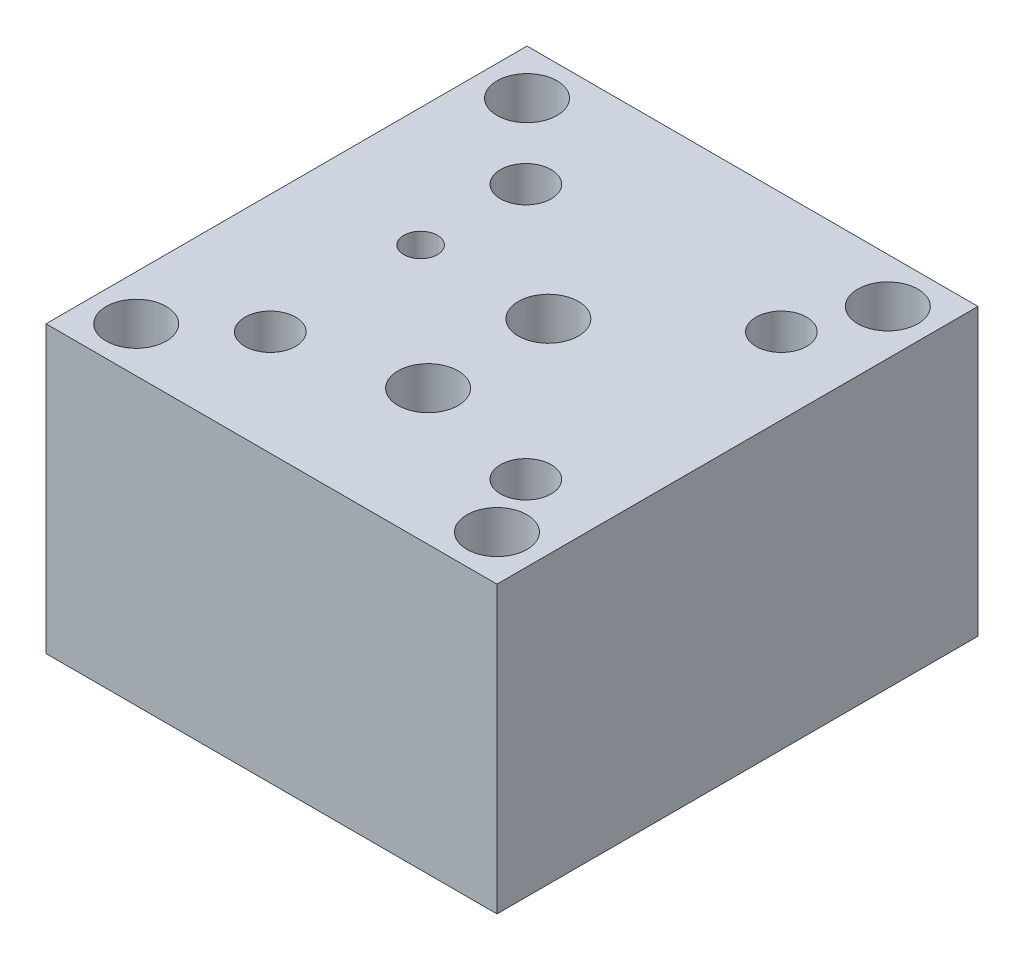
SolidWorks part; units mm, degrees
ref_plane "Front Plane" through (0, 0, 0) normal (0, 0, 1) x (1, 0, 0)
ref_plane "Top Plane" through (0, 0, 0) normal (0, 1, 0) x (1, 0, 0)
ref_plane "Right Plane" through (0, 0, 0) normal (1, 0, 0) x (0, 0, -1)
sketch "Sketch1" plane through (0, 0, 0) normal (0, 1, 0) x (1, 0, 0)
  line L1 (-47.625, -50.8) -> (47.625, -50.8)
  line L2 (-47.625, -50.8) -> (-47.625, 50.8)
  line L3 (-47.625, 50.8) -> (47.625, 50.8)
  line L4 (47.625, -50.8) -> (47.625, 50.8)
  line L5 (-47.625, -50.8) -> (47.625, 50.8) construction
  line L6 (-47.625, 50.8) -> (47.625, -50.8) construction
  point P0 (0, 0)
  dimension "D1" = 47.625
  dimension "D2" = 50.8
extrude "Boss-Extrude1" add sketch "Sketch1" along normal mid plane 60.325
sketch "Sketch2" plane through (0, 0, 0) normal (0, 1, 0) x (1, 0, 0)
  circle A0 centre (-38.1, -41.275) radius 4.3688
  circle A1 centre (38.1, -41.275) radius 4.3688
  circle A2 centre (-38.1, 41.275) radius 4.3688
  circle A3 centre (38.1, 41.275) radius 4.3688
  point P8 (0, 0)
  dimension "D1" = 8.7376
  dimension "D2" = 8.7376
  dimension "D3" = 8.7376
  dimension "D4" = 8.7376
  dimension "D5" = 76.2
  dimension "D6" = 82.55
  dimension "D7" = 38.1
  dimension "D8" = 41.275
extrude "Cut-Extrude2" cut sketch "Sketch2" against normal blind 101.6 from offset 30.1625
sketch "Sketch3" plane through (0, 0, 0) normal (0, 1, 0) x (1, 0, 0)
  circle A0 centre (-38.1, -41.275) radius 6.35
  circle A1 centre (38.1, -41.275) radius 6.35
  circle A2 centre (-38.1, 41.275) radius 6.35
  circle A3 centre (38.1, 41.275) radius 6.35
  point P8 (0, 0)
  dimension "D1" = 12.7
  dimension "D2" = 12.7
  dimension "D3" = 12.7
  dimension "D4" = 12.7
  dimension "D5" = 76.2
  dimension "D6" = 82.55
  dimension "D7" = 38.1
  dimension "D8" = 41.275
extrude "Cut-Extrude4" cut sketch "Sketch3" against normal blind 25.4 from offset 30.1625
sketch "Sketch4" plane through (0, 0, 0) normal (0, 1, 0) x (1, 0, 0)
  circle A0 centre (-22.479, -28.575) radius 5.3578
  circle A1 centre (31.496, -28.575) radius 5.3578
  circle A2 centre (-22.479, 25.4) radius 5.3578
  circle A3 centre (31.496, 25.4) radius 5.3578
  point P8 (0, 0)
  dimension "D1" = 10.7156
  dimension "D2" = 10.7156
  dimension "D3" = 10.7156
  dimension "D4" = 10.7156
  dimension "D5" = 53.975
  dimension "D6" = 53.975
  dimension "D7" = 22.479
  dimension "D8" = 28.575
extrude "Cut-Extrude6" cut sketch "Sketch4" against normal blind 20.32 from offset 30.1625
sketch "Sketch5" plane through (0, 0, 0) normal (0, 1, 0) x (1, 0, 0)
  circle A0 centre (4.5085, -22.225) radius 6.35
  circle A1 centre (4.5085, 3.175) radius 6.35
  point P4 (0, 0)
  dimension "D1" = 12.7
  dimension "D2" = 12.7
  dimension "D3" = 25.4
  dimension "D4" = 4.5085
  dimension "D5" = 22.225
extrude "Cut-Extrude8" cut sketch "Sketch5" against normal blind 45.72 from offset 30.1625
sketch "Sketch6" plane through (0, 0, 0) normal (0, 1, 0) x (1, 0, 0)
  circle A0 centre (-22.479, 3.175) radius 3.556
  point P2 (0, 0)
  dimension "D1" = 7.112
  dimension "D2" = 22.479
  dimension "D3" = 3.175
extrude "Cut-Extrude10" cut sketch "Sketch6" against normal blind 7.9375 from offset 30.1625
sketch "Sketch7" plane through (0, 0, 0) normal (1, 0, 0) x (0, 0, -1)
  circle A0 centre (-16.637, -11.1125) radius 5.5562
  point P2 (0, 0)
  dimension "D1" = 11.1125
  dimension "D2" = 16.637
  dimension "D3" = 11.1125
extrude "Cut-Extrude12" cut sketch "Sketch7" along normal blind 53.34 from offset 47.625
sketch "Sketch8" plane through (0, 0, 0) normal (0, 0, 1) x (1, 0, 0)
  circle A0 centre (10.16, -11.1125) radius 5.5562
  point P2 (0, 0)
  dimension "D1" = 11.1125
  dimension "D2" = 10.16
  dimension "D3" = 11.1125
extrude "Cut-Extrude14" cut sketch "Sketch8" along normal blind 53.34 from offset 50.8
sketch "Sketch9" plane through (0, 0, 0) normal (0, 1, 0) x (1, 0, 0)
  circle A0 centre (-28.575, -11.1125) radius 6.35
  circle A1 centre (15.875, 30.1625) radius 6.35
  point P4 (0, 0)
  dimension "D1" = 12.7
  dimension "D2" = 12.7
  dimension "D3" = 44.45
  dimension "D4" = 41.275
  dimension "D5" = 28.575
  dimension "D6" = 11.1125
extrude "Cut-Extrude16" cut sketch "Sketch9" along normal blind 27.94 from offset 30.1625
sketch "Sketch10" plane through (0, 0, 0) normal (0, 1, 0) x (1, 0, 0)
  circle A0 centre (-28.575, -11.1125) radius 12.7127
  circle A1 centre (15.875, 30.1625) radius 12.7127
  point P4 (0, 0)
  dimension "D1" = 25.4254
  dimension "D2" = 25.4254
  dimension "D3" = 44.45
  dimension "D4" = 41.275
  dimension "D5" = 28.575
  dimension "D6" = 11.1125
extrude "Cut-Extrude18" cut sketch "Sketch10" along normal blind 3.1242 from offset 30.1625
